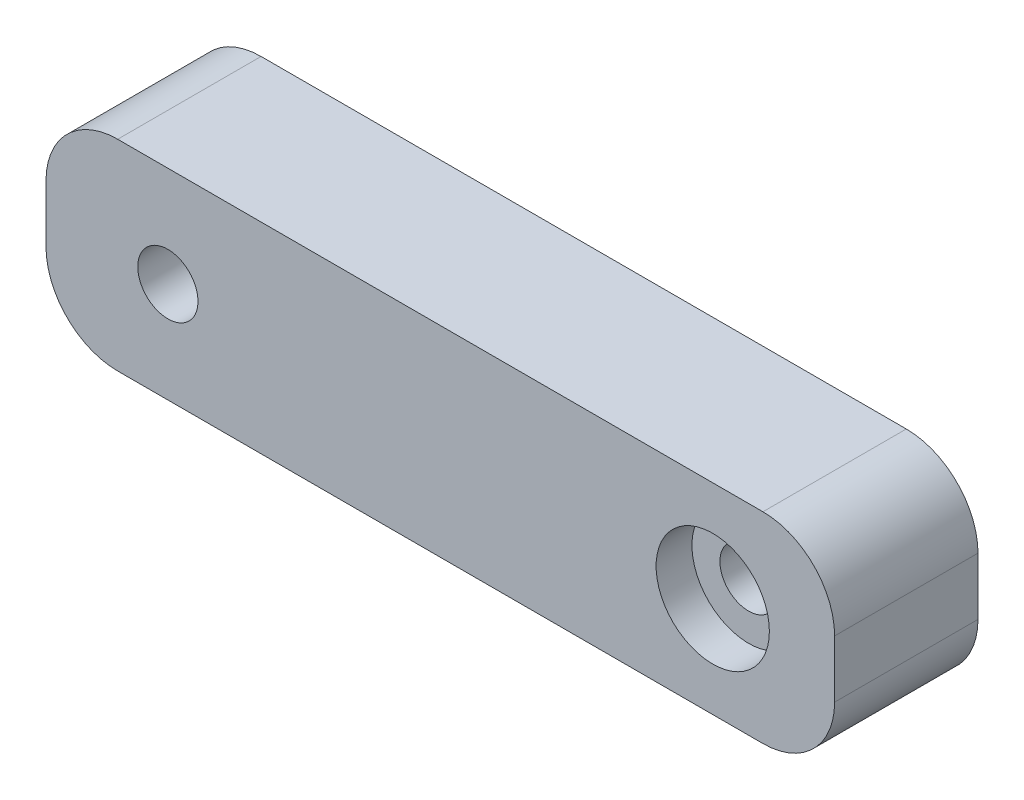
SolidWorks part; units mm, degrees
ref_plane "Front Plane" through (0, 0, 0) normal (0, 0, 1) x (1, 0, 0)
ref_plane "Top Plane" through (0, 0, 0) normal (0, 1, 0) x (1, 0, 0)
ref_plane "Right Plane" through (0, 0, 0) normal (1, 0, 0) x (0, 0, -1)
sketch "Sketch1" plane through (0, 0, 0) normal (0, 0, 1) x (1, 0, 0)
  line L1 (-59.3506, 20.3019) -> (-4.3506, 20.3019)
  line L2 (-59.3506, 20.3019) -> (-59.3506, 6.3019)
  line L3 (-59.3506, 6.3019) -> (-4.3506, 6.3019)
  line L4 (-4.3506, 20.3019) -> (-4.3506, 6.3019)
  dimension "D1" = 55
  dimension "D2" = 14
extrude "Boss-Extrude1" add sketch "Sketch1" along normal blind 10 contours L1 L4 L3 L2
fillet "Fillet1" radius 5 1 edges at (-59.3506, 20.3019, 5)
fillet "Fillet2" radius 5 3 edges at (-4.3506, 6.3019, 5) (-4.3506, 20.3019, 5) (-59.3506, 6.3019, 5)
sketch "Sketch2" plane through (0, 0, 0) normal (0, 0, -1) x (-1, 0, 0)
  line L0 (59.3506, 15.3019) -> (59.3506, 11.3019) construction
  line L1 (54.3506, 20.3019) -> (9.3506, 20.3019) construction
  circle A0 centre (50.8506, 13.3019) radius 4
  point P4 (59.3506, 13.3019)
  dimension "D1" = 8.5
  dimension "D2" = 7
extrude "Cut-Extrude2" cut sketch "Sketch2" against normal blind 2.5 contours A0
sketch "Sketch3" plane through (0, 0, 2.5) normal (0, 0, -1) x (-1, 0, 0)
  circle A2 centre (50.8506, 13.3019) radius 2.1
extrude "Cut-Extrude3" cut sketch "Sketch3" against normal blind 2 contours A2
sketch "Sketch4" plane through (0, 0, 10) normal (0, 0, 1) x (1, 0, 0)
  line L0 (-4.3506, 15.3019) -> (-4.3506, 11.3019) construction
  line L1 (-54.3506, 20.3019) -> (-9.3506, 20.3019) construction
  circle A0 centre (-12.8506, 13.3019) radius 3.95
  dimension "D1" = 8.5
  dimension "D2" = 7
extrude "Cut-Extrude4" cut sketch "Sketch4" against normal blind 5 contours A0
sketch "Sketch5" plane through (0, 0, 5) normal (0, 0, 1) x (1, 0, 0)
  circle A0 centre (-12.8506, 13.3019) radius 2
extrude "Cut-Extrude5" cut sketch "Sketch5" against normal up to next contours A0
sketch "Sketch6" plane through (0, 0, 0) normal (0, 0, -1) x (-1, 0, 0)
  circle A0 centre (12.8506, 13.3019) radius 2.1
  circle A1 centre (12.8506, 13.3019) radius 3.5
sketch "Sketch7" plane through (0, 0, 4.5) normal (0, 0, -1) x (-1, 0, 0)
  circle A0 centre (50.8506, 13.3019) radius 2.1
extrude "Cut-Extrude6" cut sketch "Sketch7" against normal through all
sketch "Sketch9" plane through (0, 0, 5) normal (0, 0, 1) x (1, 0, 0)
  circle A0 centre (-12.8506, 13.3019) radius 2 construction
  circle A1 centre (-12.8506, 13.3019) radius 3.95
  circle A2 centre (-12.8506, 13.3019) radius 3.95
  circle A3 centre (-12.8506, 13.3019) radius 2
  dimension "D1" = 0
extrude "Boss-Extrude2" add sketch "Sketch9" along normal blind 2.5
sketch "Sketch10" plane through (0, 0, 0) normal (0, 0, -1) x (-1, 0, 0)
  line L0 (12.8506, 13.3019) -> (12.8506, 17.3434) construction
  line L1 (12.8506, 13.3019) -> (12.8506, 9.2605) construction
  line L2 (12.8506, 17.3434) -> (17.9153, 20.2675) construction
  line L3 (12.8506, 17.3434) -> (9.3506, 15.3227)
  line L4 (9.3506, 15.3227) -> (9.3506, 11.2812)
  line L5 (9.3506, 11.2812) -> (12.8506, 9.2605)
  line L6 (12.8506, 17.3434) -> (26.8538, 9.2587) construction
  line L7 (12.8506, 17.3434) -> (16.3506, 15.3227)
  line L8 (16.3506, 15.3227) -> (16.3506, 11.2812)
  line L9 (16.3506, 11.2812) -> (12.8506, 9.2605)
  line L10 (9.3506, 13.3019) -> (16.3506, 13.3019) construction
  circle A0 centre (12.8506, 13.3019) radius 2 construction
  circle A1 centre (12.8506, 13.3019) radius 2
  point P14 (12.8506, 13.3019)
  dimension "D1" = 7
  dimension "D4" = 60
extrude "Cut-Extrude7" cut sketch "Sketch10" against normal blind 3
